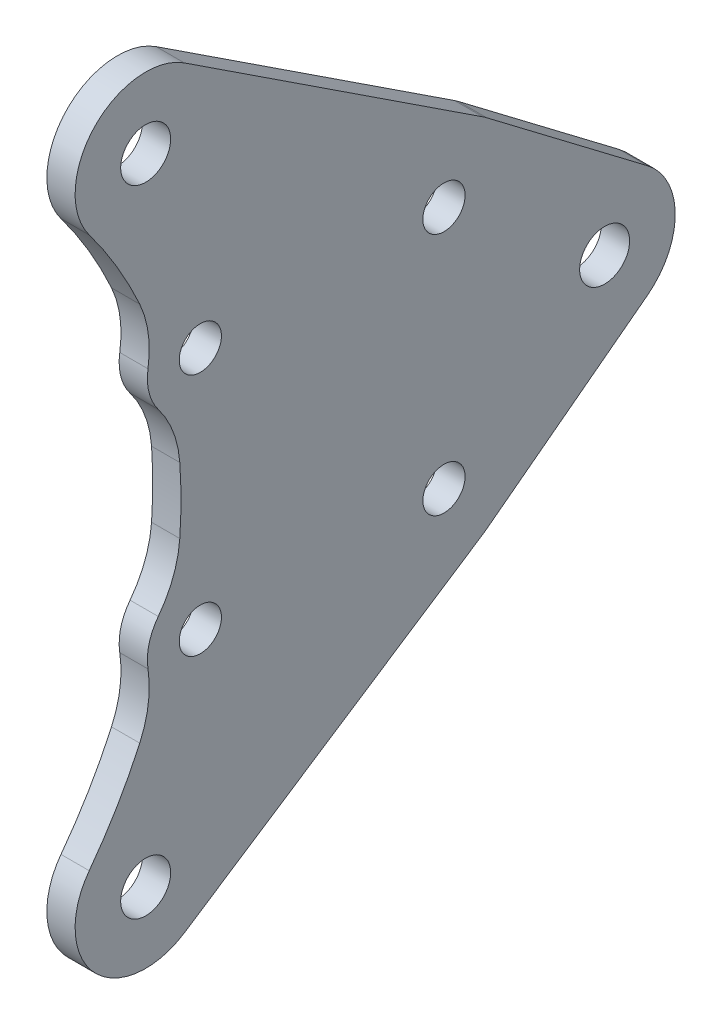
SolidWorks part; units mm, degrees
ref_plane "Front" through (0, 0, 0) normal (0, 0, 1) x (1, 0, 0)
ref_plane "Top" through (0, 0, 0) normal (0, 1, 0) x (1, 0, 0)
ref_plane "Right" through (0, 0, 0) normal (1, 0, 0) x (0, 0, -1)
sketch "Sketch1" plane through (0, 0, 0) normal (1, 0, 0) x (0, 0, -1)
  line L5 (29.2497, 5.0597) -> (14.7971, 16.0198)
  line L6 (29.2497, -5.0597) -> (14.7971, -16.0198)
  line L9 (14.4447, -16.2686) -> (-12.3904, -33.8835)
  line L10 (14.4447, 16.2686) -> (-12.3904, 33.8835)
  arc A0 (-20.955, -24.765) -> (-12.3904, -33.8835) centre (-15.875, -28.575) ccw
  arc A1 (29.2497, -5.0597) -> (29.2497, 5.0597) centre (25.4127, 0) ccw
  arc A2 (-12.3904, 33.8835) -> (-20.955, 24.765) centre (-15.875, 28.575) ccw
  arc A3 (14.4447, -16.2686) -> (14.7971, -16.0198) centre (10.9601, -10.9601) ccw
  arc A4 (14.7971, 16.0198) -> (14.4447, 16.2686) centre (10.9601, 10.9601) ccw
  arc A5 (-20.955, -24.765) -> (-16.4091, -17.1005) centre (-53.975, 0) ccw
  circle A6 centre (-53.975, 0) radius 32.3977 construction
  arc A7 (-14.7423, -8.0659) -> (-15.6661, -11.6915) centre (-10.9601, -10.9601) ccw
  circle A8 centre (-10.9601, -10.9601) radius 1.7526 construction
  arc A9 (-15.6661, 11.6915) -> (-14.7423, 8.0659) centre (-10.9601, 10.9601) ccw
  circle A10 centre (-10.9601, 10.9601) radius 1.7526 construction
  arc A11 (-16.4091, 17.1005) -> (-20.955, 24.765) centre (-53.975, 0) ccw
  arc A12 (-12.8063, -2.9609) -> (-12.8063, 2.9609) centre (-53.975, 0) ccw
  arc A13 (-15.6661, 11.6915) -> (-16.4091, 17.1005) centre (-25.0781, 13.1542) ccw
  arc A14 (-14.7423, 8.0659) -> (-12.8063, 2.9609) centre (-22.3068, 2.2776) cw
  arc A15 (-14.7423, -8.0659) -> (-12.8063, -2.9609) centre (-22.3068, -2.2776) ccw
  arc A16 (-15.6661, -11.6915) -> (-16.4091, -17.1005) centre (-25.0781, -13.1542) cw
  point P37 (-14.9768, 13.519)
  point P42 (-13.2625, -6.7911)
  dimension "D1" = 12.7
  dimension "D2" = 12.7
  dimension "D3" = 9.525
  dimension "D4" = 9.525
extrude "Boss-Extrude1" add sketch "Sketch1" along normal blind 2.54
hole_wizard "#8 Clearance Hole1" positions "Sketch2" profile "Sketch3" hole size "#8" standard "ANSI Inch" end condition through all
sketch "Sketch2" plane through (2.54, 0, 0) normal (1, 0, 0) x (0, 0, -1)
  point P0 (-15.875, 28.575)
  point P2 (25.4127, 0)
  point P4 (-15.875, -28.575)
sketch "Sketch3" plane through (2.54, 28.575, 15.875) normal (0, 1, 0) x (0, 0, -1)
  line L0 (0, 0) -> (0, 2.54)
  line L1 (0, 2.54) -> (2.2479, 2.54)
  line L2 (2.2479, 2.54) -> (2.2479, 0)
  line L5 (2.2479, 0) -> (0, 0)
  line L11 (0, -6.35) -> (0, 107.95) construction
  dimension "Thru Hole Dia." = 4.4958
  dimension "Thru Hole Depth" = 2.54
hole_wizard "#6 Clearance Hole1" positions "Sketch4" profile "Sketch5" hole size "#6" standard "ANSI Inch" end condition through all
sketch "Sketch4" plane through (2.54, 0, 0) normal (1, 0, 0) x (0, 0, -1)
  circle A0 centre (10.9601, 10.9601) radius 1.7526 construction
  circle A1 centre (10.9601, -10.9601) radius 1.7526 construction
  circle A2 centre (-10.9601, -10.9601) radius 1.7526 construction
  circle A3 centre (-10.9601, 10.9601) radius 1.7526 construction
  point P0 (-10.9601, 10.9601)
  point P2 (10.9601, 10.9601)
  point P4 (-10.9601, -10.9601)
  point P6 (10.9601, -10.9601)
sketch "Sketch5" plane through (2.54, 10.9601, 10.9601) normal (0, 1, 0) x (0, 0, -1)
  line L0 (0, 0) -> (0, 2.54)
  line L1 (0, 2.54) -> (1.8986, 2.54)
  line L2 (1.8986, 2.54) -> (1.8986, 0)
  line L5 (1.8986, 0) -> (0, 0)
  line L11 (0, -6.35) -> (0, 107.95) construction
  dimension "Thru Hole Dia." = 3.7973
  dimension "Thru Hole Depth" = 2.54
